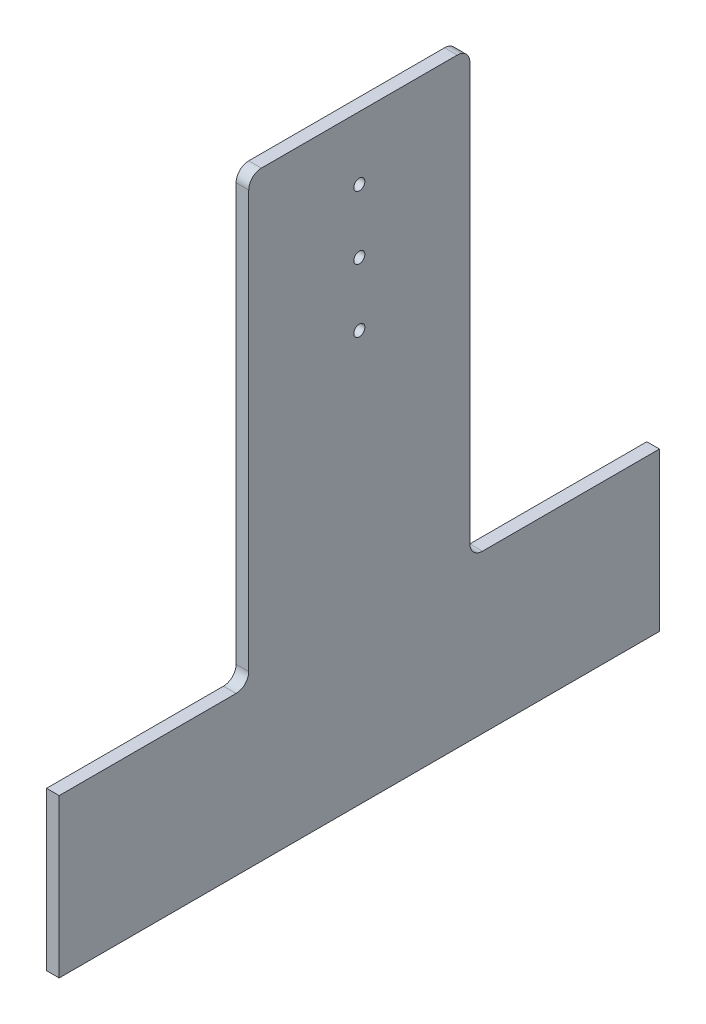
SolidWorks part; units mm, degrees
ref_plane "Front Plane" through (0, 0, 0) normal (0, 0, 1) x (1, 0, 0)
ref_plane "Top Plane" through (0, 0, 0) normal (0, 1, 0) x (1, 0, 0)
ref_plane "Right Plane" through (0, 0, 0) normal (1, 0, 0) x (0, 0, -1)
sketch "Sketch1" plane through (0, 0, 0) normal (1, 0, 0) x (0, 0, -1)
  line L0 (35, 25) -> (95, 25)
  line L1 (-95, 25) -> (-35, 25)
  line L2 (-95, 25) -> (-95, -25)
  line L3 (-95, -25) -> (95, -25)
  line L4 (95, 25) -> (95, -25)
  line L5 (-95, 25) -> (95, -25) construction
  line L6 (-95, -25) -> (95, 25) construction
  line L7 (-35, 165) -> (35, 165)
  line L8 (-35, 165) -> (-35, 25)
  line L10 (35, 165) -> (35, 25)
  line L11 (-35, 165) -> (35, 25) construction
  line L12 (-35, 25) -> (35, 165) construction
  circle A0 centre (0, 145) radius 1.75
  circle A1 centre (0, 125) radius 1.75
  circle A2 centre (0, 105) radius 1.75
  point P0 (0, 0)
  point P6 (0, 95)
  dimension "D6" = 3.5
  dimension "D1" = 50
  dimension "D2" = 190
  dimension "D3" = 140
  dimension "D4" = 70
  dimension "D5" = 60
  dimension "D7" = 35
  dimension "D8" = 20
  dimension "D10" = 10
  dimension "D9" = 3
extrude "Boss-Extrude1" add sketch "Sketch1" along normal blind 4
fillet "Fillet1" radius 4 4 edges at (2, 25, -35) (2, 165, -35) (2, 165, 35) (2, 25, 35)
